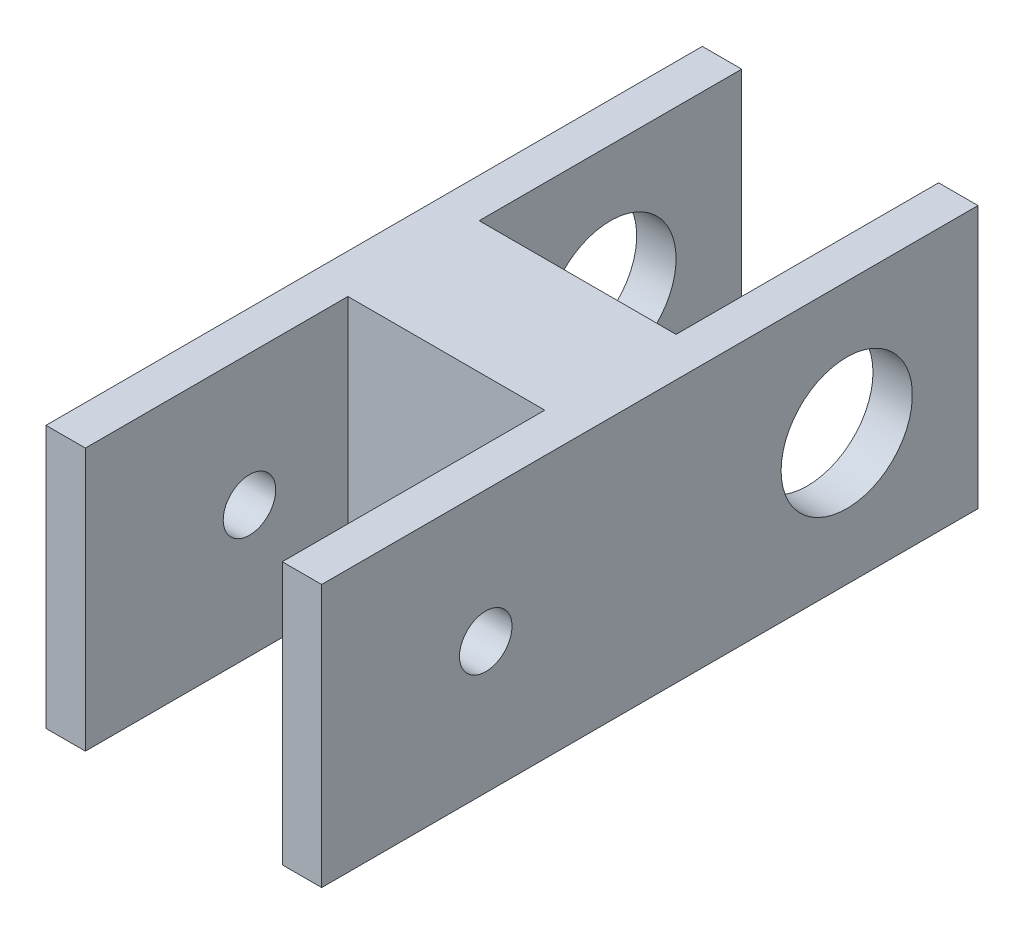
SolidWorks part; units mm, degrees
material "Custom Plastic"
ref_plane "Front Plane" through (0, 0, 0) normal (0, 0, 1) x (1, 0, 0)
ref_plane "Top Plane" through (0, 0, 0) normal (0, 1, 0) x (1, 0, 0)
ref_plane "Right Plane" through (0, 0, 0) normal (1, 0, 0) x (0, 0, -1)
sketch "Sketch1" plane through (0, 0, 0) normal (0, 1, 0) x (1, 0, 0)
  line L0 (75, -250) -> (105, -250)
  line L1 (-105, 250) -> (-75, 250)
  line L2 (-105, 250) -> (-105, -250)
  line L3 (-105, -250) -> (-75, -250)
  line L4 (105, 250) -> (105, -250)
  line L5 (-105, 250) -> (105, -250) construction
  line L6 (-105, -250) -> (105, 250) construction
  line L8 (-75, -250) -> (-75, -50)
  line L9 (-75, -50) -> (75, -50)
  line L10 (75, -250) -> (75, -50)
  line L12 (-75, 250) -> (-75, 50)
  line L13 (-75, 50) -> (75, 50)
  line L14 (75, 250) -> (75, 50)
  line L15 (75, 250) -> (105, 250)
  point P0 (0, 0)
  dimension "D1" = 200
  dimension "D2" = 150
  dimension "D3" = 30
  dimension "D4" = 30
  dimension "D5" = 100
  dimension "D6" = 200
extrude "Boss-Extrude1" add sketch "Sketch1" along normal blind 200
sketch "Sketch4" plane through (-105, 0, 0) normal (-1, 0, 0) x (0, 0, 1)
  line L1 (250, 200) -> (250, 0) construction
  line L2 (-250, 200) -> (-250, 0) construction
  circle A0 centre (125, 100) radius 20
  circle A1 centre (-150, 100) radius 50
  dimension "D1" = 40
  dimension "D3" = 100
  dimension "D2" = 125
  dimension "D4" = 100
extrude "Cut-Extrude1" cut sketch "Sketch4" against normal blind 313
scale "Scale1" scale about centroid uniform scaling yes scale factor 0.75
